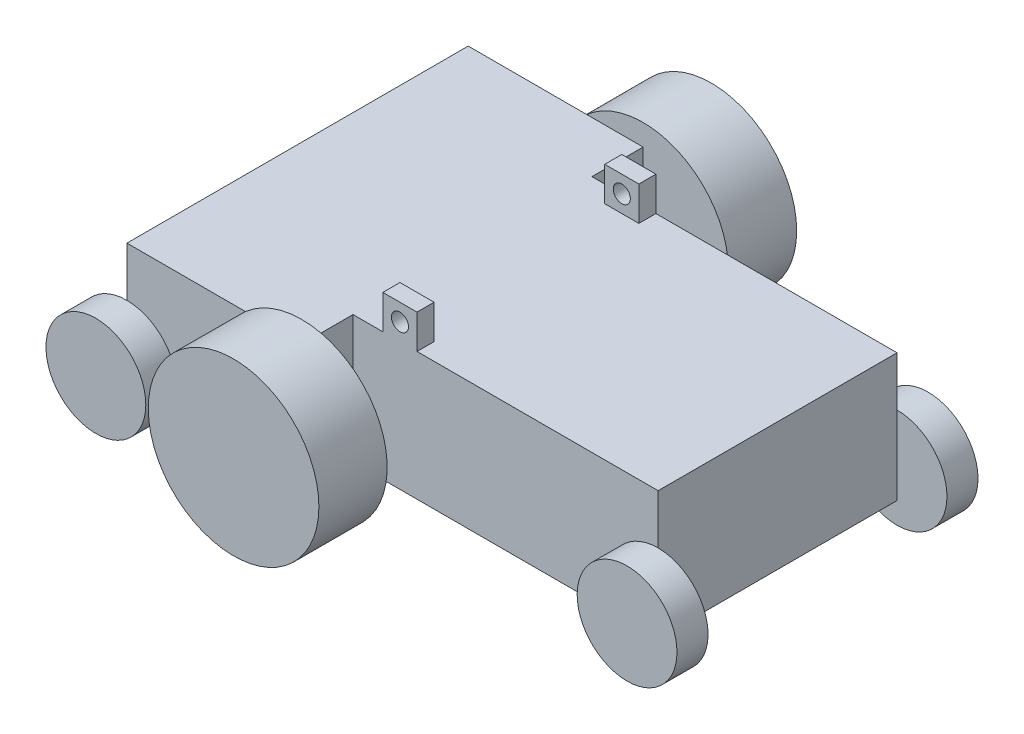
SolidWorks part; units mm, degrees
ref_plane "Front Plane" through (0, 0, 0) normal (0, 0, 1) x (1, 0, 0)
ref_plane "Top Plane" through (0, 0, 0) normal (0, 1, 0) x (1, 0, 0)
ref_plane "Right Plane" through (0, 0, 0) normal (1, 0, 0) x (0, 0, -1)
other "Center of Mass"
sketch "Sketch1" plane through (0, 0, 0) normal (0, 1, 0) x (1, 0, 0)
  line L0 (260.35, 508) -> (260.35, 431.8)
  line L1 (0, 0) -> (260.35, 0)
  line L2 (0, 0) -> (0, 508)
  line L3 (0, 508) -> (260.35, 508)
  line L4 (714.502, 431.8) -> (714.502, 76.2)
  line L5 (260.35, 431.8) -> (714.502, 431.8)
  line L6 (260.35, 0) -> (260.35, 76.2)
  line L7 (260.35, 76.2) -> (714.502, 76.2)
  line L8 (-87.8876, 254) -> (946.8648, 254) construction
  dimension "D1" = 355.6
  dimension "D2" = 254
  dimension "D3" = 714.502
  dimension "D4" = 454.152
extrude "Boss-Extrude1" add sketch "Sketch1" along normal blind 190.5
sketch "Sketch2" plane through (0, 0, 0) normal (0, 0, 1) x (1, 0, 0)
  line L0 (260.35, 190.5) -> (260.35, 0) construction
  circle A0 centre (260.35, 95.25) radius 127
  dimension "D1" = 254
extrude "Boss-Extrude2" add sketch "Sketch2" along normal blind 101.6
sketch "Sketch3" plane through (0, 0, 0) normal (0, 0, 1) x (1, 0, 0)
  line L0 (0, 190.5) -> (0, 0) construction
  circle A0 centre (0, 42.418) radius 74.295
  dimension "D2" = 148.59
  dimension "D1" = 52.832
extrude "Boss-Extrude3" add sketch "Sketch3" along normal blind 46.228
sketch "Sketch4" plane through (0, 0, -76.2) normal (0, 0, 1) x (1, 0, 0)
  line L0 (714.502, 190.5) -> (714.502, 0) construction
  circle A0 centre (714.502, 42.418) radius 74.295
  dimension "D1" = 148.59
  dimension "D2" = 52.832
extrude "Boss-Extrude4" add sketch "Sketch4" along normal blind 46.228
ref_plane "Plane1" through (0, 0, -254) normal (0, 0, 1) x (1, 0, 0)
mirror "Mirror1" about plane through (0, 0, -254) normal (0, 0, 1) of "Boss-Extrude4", "Boss-Extrude3", "Boss-Extrude2"
ref_plane "Plane2" through (330.2, 0, 0) normal (-1, 0, 0) x (0, 0, 1)
sketch "Sketch6" plane through (330.2, 0, 0) normal (-1, 0, 0) x (0, 0, 1)
  line L0 (-508, 190.5) -> (0, 190.5) construction
  line L1 (-101.6, 190.5) -> (-76.2, 190.5)
  line L2 (-101.6, 190.5) -> (-101.6, 241.3)
  line L3 (-101.6, 241.3) -> (-76.2, 241.3)
  line L4 (-76.2, 190.5) -> (-76.2, 241.3)
  line L6 (-254, -96.9911) -> (-254, 96.9911) construction
  dimension "D1" = 25.4
  dimension "D2" = 50.8
  dimension "D3" = 152.4
extrude "Boss-Extrude5" add sketch "Sketch6" along normal blind 25.4 and the other way blind 25.4
sketch "Sketch7" plane through (0, 0, -101.6) normal (0, 0, -1) x (-1, 0, 0)
  line L0 (-330.2, -165.2843) -> (-330.2, 165.2843) construction
  line L1 (-355.6, 241.3) -> (-304.8, 241.3) construction
  circle A0 centre (-330.2, 215.9) radius 12.7
  dimension "D2" = 25.4
  dimension "D1" = 25.4
extrude "Cut-Extrude1" cut sketch "Sketch7" against normal blind 73.152
mirror "Mirror2" about plane through (0, 0, -254) normal (0, 0, 1) of "Cut-Extrude1", "Boss-Extrude5"
ref_plane "Plane3" through (330.2, 0, 0) normal (-1, 0, 0) x (0, 0, 1)
sketch "Sketch8" plane through (330.2, 0, 0) normal (-1, 0, 0) x (0, 0, 1)
  line L0 (-101.6, 215.9) -> (-515.347, 215.9) construction
